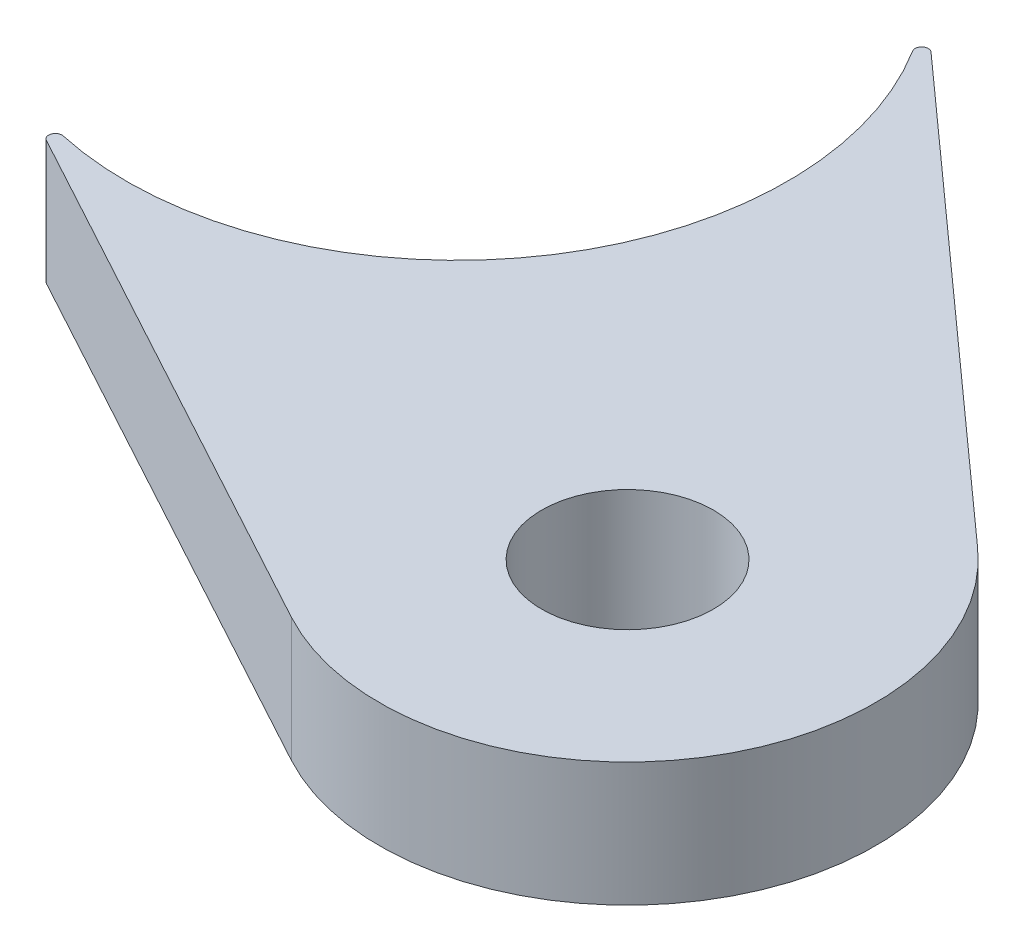
SolidWorks part; units mm, degrees
material "AISI 4130 Steel, annealed at 865C"
ref_plane "X-Y Datum" through (0, 0, 0) normal (0, 0, 1) x (1, 0, 0)
ref_plane "X-Z Datum" through (0, 0, 0) normal (0, 1, 0) x (1, 0, 0)
ref_plane "Y-Z Datum" through (0, 0, 0) normal (1, 0, 0) x (0, 0, -1)
sketch "Sketch1" plane through (0, 0, 0) normal (0, 1, 0) x (1, 0, 0)
  line L0 (17.6706, -24.0334) -> (-6.0555, -11.1634)
  line L1 (28.5727, -8.5707) -> (8.4806, 9.4535)
  circle A2 centre (22.2122, -15.6608) radius 3.3
  circle A3 centre (0, 0) radius 12.7 construction
  circle A4 centre (22.2122, -15.6608) radius 9.525 construction
  arc A6 (28.5727, -8.5707) -> (17.6706, -24.0334) centre (22.2122, -15.6608) cw
  arc A7 (-6.0555, -11.1634) -> (8.4806, 9.4535) centre (0, 0) ccw
  dimension "D3" = 25.4
  dimension "D4" = 19.05
  dimension "D5" = 6.6
  dimension "D1" = 15.6608
  dimension "D2" = 22.2122
extrude "Boss-Extrude1" add sketch "Sketch1" along normal blind 4.7625
fillet "Fillet1" radius 0.254 2 edges at (8.4806, 2.3813, -9.4535) (-6.0555, 2.3813, 11.1634)
